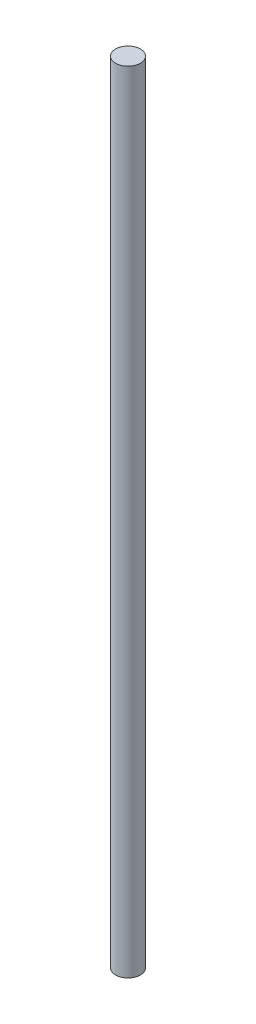
SolidWorks part; units mm, degrees
material "acero"
ref_plane "Alzado" through (0, 0, 0) normal (0, 0, 1) x (1, 0, 0)
ref_plane "Planta" through (0, 0, 0) normal (0, 1, 0) x (1, 0, 0)
ref_plane "Vista lateral" through (0, 0, 0) normal (1, 0, 0) x (0, 0, -1)
sketch "Croquis1" plane through (0, 0, 0) normal (0, 1, 0) x (1, 0, 0)
  circle A0 centre (0, 0) radius 4
  dimension "D1" = 8
extrude "Saliente-Extruir1" add sketch "Croquis1" along normal blind 255
